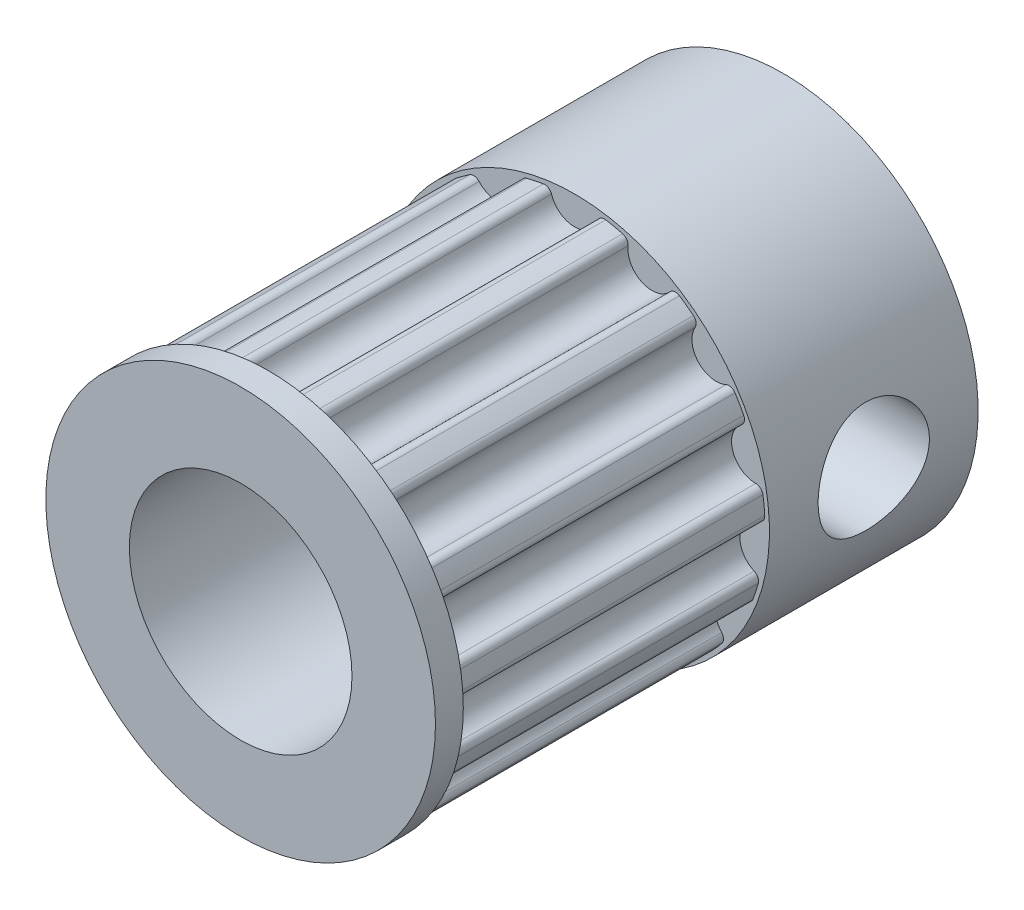
SolidWorks part; units mm, degrees
material "PLA+"
ref_plane "Front Plane" through (0, 0, 0) normal (0, 0, 1) x (1, 0, 0)
ref_plane "Top Plane" through (0, 0, 0) normal (0, 1, 0) x (1, 0, 0)
ref_plane "Right Plane" through (0, 0, 0) normal (1, 0, 0) x (0, 0, -1)
sketch "Sketch1" plane through (0, 0, 0) normal (0, 0, 1) x (1, 0, 0)
  circle A0 centre (0, 0) radius 7.162 construction
  circle A1 centre (0, 0) radius 6.844
  dimension "D1" = 14.3239
  dimension "D2" = 0.318
extrude "Boss-Extrude1" add sketch "Sketch1" along normal mid plane 11
sketch "Sketch2" plane through (0, 0, 5.5) normal (0, 0, 1) x (1, 0, 0)
  line L0 (0, 0) -> (0, 6.844) construction
  circle A0 centre (0, 0) radius 6.844 construction
  circle A1 centre (0, 6.844) radius 0.87 construction
  circle A2 centre (-1.075, 6.4956) radius 0.26 construction
  arc A3 (-1.1174, 6.7521) -> (-0.8276, 6.5758) centre (-1.075, 6.4956) cw
  arc A4 (-0.8276, 6.5758) -> (0.8276, 6.5758) centre (0, 6.844) ccw
  arc A5 (1.1174, 6.7521) -> (0.8276, 6.5758) centre (1.075, 6.4956) ccw
  arc A6 (-1.1174, 6.7521) -> (1.1174, 6.7521) centre (0, 0) cw
  dimension "D1" = 1.74
  dimension "D2" = 0.52
extrude "Cut-Extrude1" cut sketch "Sketch2" against normal through all
pattern_circular "CirPattern1" count 15 over 360 about axis through (0, 0, 0) along (0, 0, 1) of "Cut-Extrude1"
sketch "Sketch3" plane through (0, 0, 5.5) normal (0, 0, 1) x (1, 0, 0)
  circle A0 centre (0, 0) radius 7
  dimension "D1" = 14
extrude "Boss-Extrude2" add sketch "Sketch3" along normal blind 1
sketch "Sketch4" plane through (0, 0, -5.5) normal (0, 0, -1) x (-1, 0, 0)
  circle A0 centre (0, 0) radius 7
  dimension "D1" = 14
extrude "Boss-Extrude3" add sketch "Sketch4" along normal blind 7.5
sketch "Sketch5" plane through (0, 0, 6.5) normal (0, 0, 1) x (1, 0, 0)
  circle A0 centre (0, 0) radius 4
  dimension "D1" = 8
extrude "Cut-Extrude2" cut sketch "Sketch5" against normal through all
sketch "Sketch6" plane through (0, 0, 0) normal (1, 0, 0) x (0, 0, -1)
  line L0 (13, 0) -> (5.5, 0) construction
  line L1 (13, -4) -> (13, 4) construction
  line L2 (5.5, 0.1357) -> (5.5, -1.5105) construction
  circle A0 centre (9.25, 0) radius 2
  dimension "D1" = 4
extrude "Cut-Extrude3" cut sketch "Sketch6" along normal through all
pattern_circular "CirPattern2" count 2 over 90 about axis through (0, 0, -13) along (0, 0, 1) of "Cut-Extrude3"
